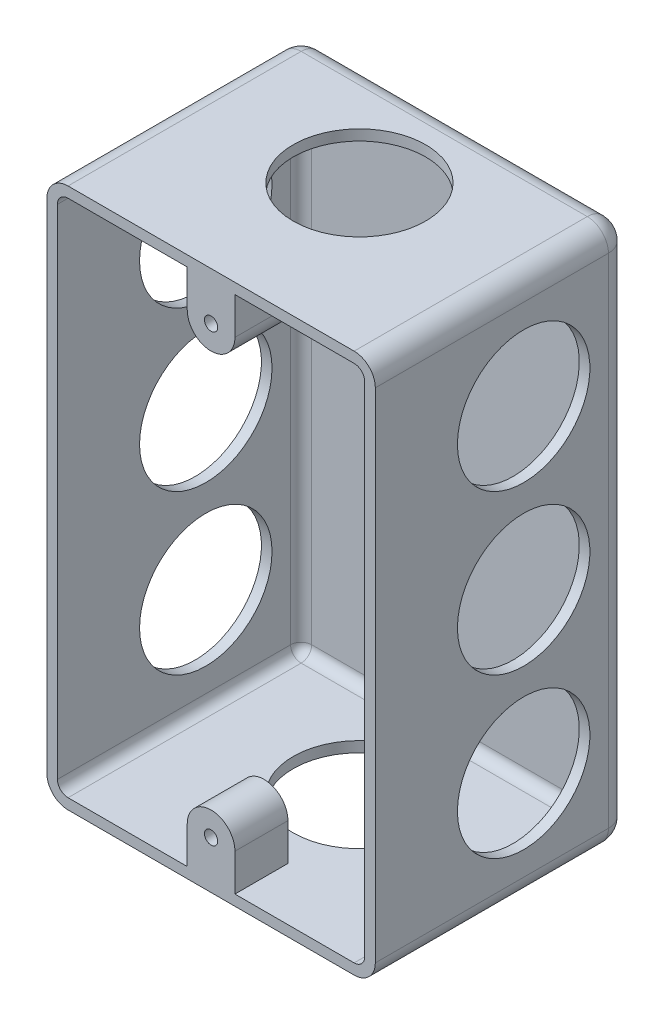
SolidWorks part; units mm, degrees
ref_plane "Plano frontal" through (0, 0, 0) normal (0, 0, 1) x (1, 0, 0)
ref_plane "Plano superior" through (0, 0, 0) normal (0, 1, 0) x (1, 0, 0)
ref_plane "Plano direito" through (0, 0, 0) normal (1, 0, 0) x (0, 0, -1)
sketch "Esboço1" plane through (0, 0, 0) normal (0, 0, 1) x (1, 0, 0)
  line L1 (-31, -51) -> (31, -51)
  line L2 (-31, -51) -> (-31, 51)
  line L3 (-31, 51) -> (31, 51)
  line L4 (31, -51) -> (31, 51)
  line L5 (-31, -51) -> (31, 51) construction
  line L6 (-31, 51) -> (31, -51) construction
  point P0 (0, 0)
  dimension "D1" = 102
  dimension "D2" = 62
extrude "Ressalto-extrusão1" add sketch "Esboço1" along normal blind 48
fillet "Filete1" radius 4 8 edges at (-31, -51, 24) (31, -51, 24) (31, 51, 24) (-31, 51, 24) (0, 51, 0) (-31, 0, 0) (0, -51, 0) (31, 0, 0)
shell "Casca1" thickness 2
sketch "Esboço2" plane through (-31, 0, 0) normal (-1, 0, 0) x (0, 0, 1)
  line L0 (0, -47) -> (0, 47) construction
  circle A0 centre (20, 0) radius 12.5
  circle A1 centre (20, 30) radius 12.5
  circle A2 centre (20, -30) radius 12.5
  dimension "D1" = 25
  dimension "D2" = 20
  dimension "D3" = 2
  dimension "D4" = 2
extrude "Corte-extrusão1" cut sketch "Esboço2" against normal through all
sketch "Esboço3" plane through (0, 51, 0) normal (0, 1, 0) x (1, 0, 0)
  line L0 (-27, 0) -> (27, 0) construction
  circle A0 centre (0, -20) radius 12.5
  dimension "D1" = 25
  dimension "D2" = 20
extrude "Corte-extrusão2" cut sketch "Esboço3" against normal through all
sketch "Esboço4" plane through (0, 0, 48) normal (0, 0, 1) x (1, 0, 0)
  line L0 (-4.5, 42) -> (-4.5, 49)
  line L1 (27, 49) -> (-27, 49) construction
  line L2 (4.5, 42) -> (4.5, 49)
  line L3 (4.5, 49) -> (-4.5, 49)
  line L4 (-31, 0) -> (31, 0) construction
  line L5 (-31, 47) -> (-31, -47) construction
  line L6 (31, -47) -> (31, 47) construction
  line L7 (4.5, -49) -> (-4.5, -49)
  line L8 (4.5, -42) -> (4.5, -49)
  line L9 (-4.5, -42) -> (-4.5, -49)
  circle A0 centre (0, 42) radius 1.25
  arc A1 (-4.5, 42) -> (4.5, 42) centre (0, 42) ccw
  arc A2 (-4.5, -42) -> (4.5, -42) centre (0, -42) cw
  circle A3 centre (0, -42) radius 1.25
  dimension "D1" = 42
  dimension "D2" = 2.5
  dimension "D3" = 9
extrude "Ressalto-extrusão2" add sketch "Esboço4" against normal blind 10
